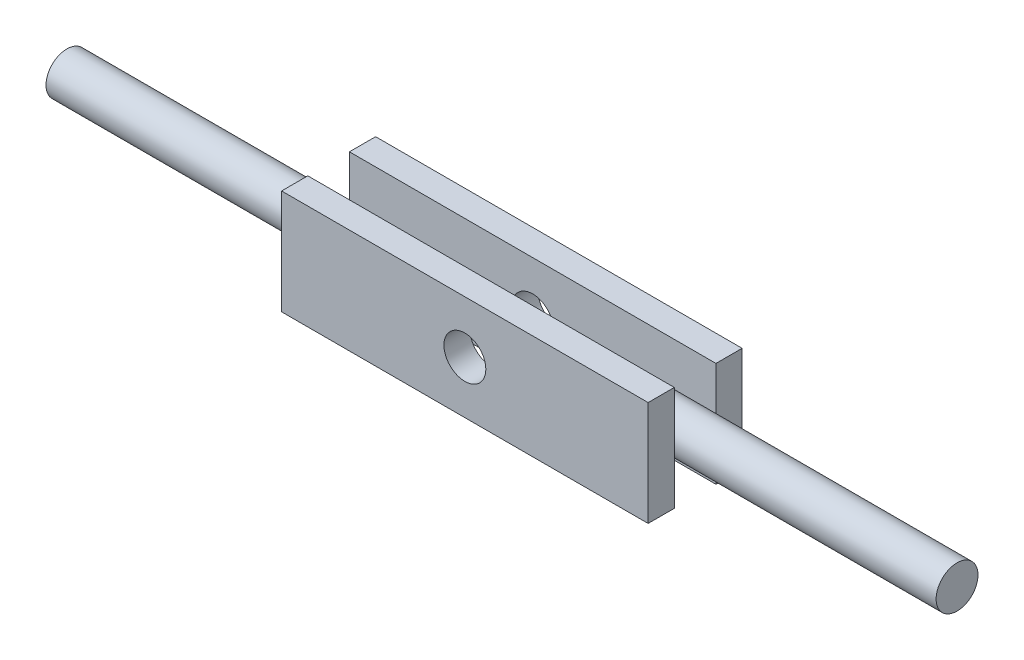
SolidWorks part; units mm, degrees
material "ASTM A36"
ref_plane "Front Plane" through (0, 0, 0) normal (0, 0, 1) x (1, 0, 0)
ref_plane "Top Plane" through (0, 0, 0) normal (0, 1, 0) x (1, 0, 0)
ref_plane "Right Plane" through (0, 0, 0) normal (1, 0, 0) x (0, 0, -1)
sketch "Sketch1" plane through (0, 0, 0) normal (0, 0, 1) x (1, 0, 0)
  line L1 (70, -20) -> (-70, -20)
  line L2 (70, -20) -> (70, 20)
  line L3 (70, 20) -> (-70, 20)
  line L4 (-70, -20) -> (-70, 20)
  line L5 (70, -20) -> (-70, 20) construction
  line L6 (70, 20) -> (-70, -20) construction
  point P0 (0, 0)
  dimension "D1" = 40
  dimension "D2" = 140
extrude "Boss-Extrude1" add sketch "Sketch1" along normal blind 10
sketch "Sketch4" plane through (0, 0, 10) normal (0, 0, 1) x (1, 0, 0)
  line L0 (-70, 20) -> (-70, -20) construction
  circle A0 centre (0, 0) radius 8
  dimension "D2" = 16
  dimension "D1" = 70
extrude "Cut-Extrude1" cut sketch "Sketch4" against normal blind 10
sketch "Sketch5" plane through (70, 0, 0) normal (1, 0, 0) x (0, 0, -1)
  line L0 (0, -20) -> (0, 20) construction
  circle A0 centre (8, 0) radius 8
  dimension "D1" = 16
  dimension "D2" = 8
extrude "Boss-Extrude2" add sketch "Sketch5" along normal blind 100 and the other way blind 20 separate body
pattern_linear "LPattern1" count 2 spacing 25.9 along (0, 0, -1) of "Boss-Extrude1"
sketch "Sketch6" plane through (0, 0, -25.9) normal (0, 0, -1) x (-1, 0, 0)
  line L0 (70, 20) -> (70, -20) construction
  circle A0 centre (0, 0) radius 8
  dimension "D1" = 70
  dimension "D2" = 16
extrude "Cut-Extrude2" cut sketch "Sketch6" against normal blind 100
sketch "Sketch7" plane through (-70, 0, 0) normal (-1, 0, 0) x (0, 0, 1)
  circle A0 centre (-8, 0) radius 8
extrude "Boss-Extrude3" add sketch "Sketch7" along normal blind 100 and the other way blind 20 separate body
